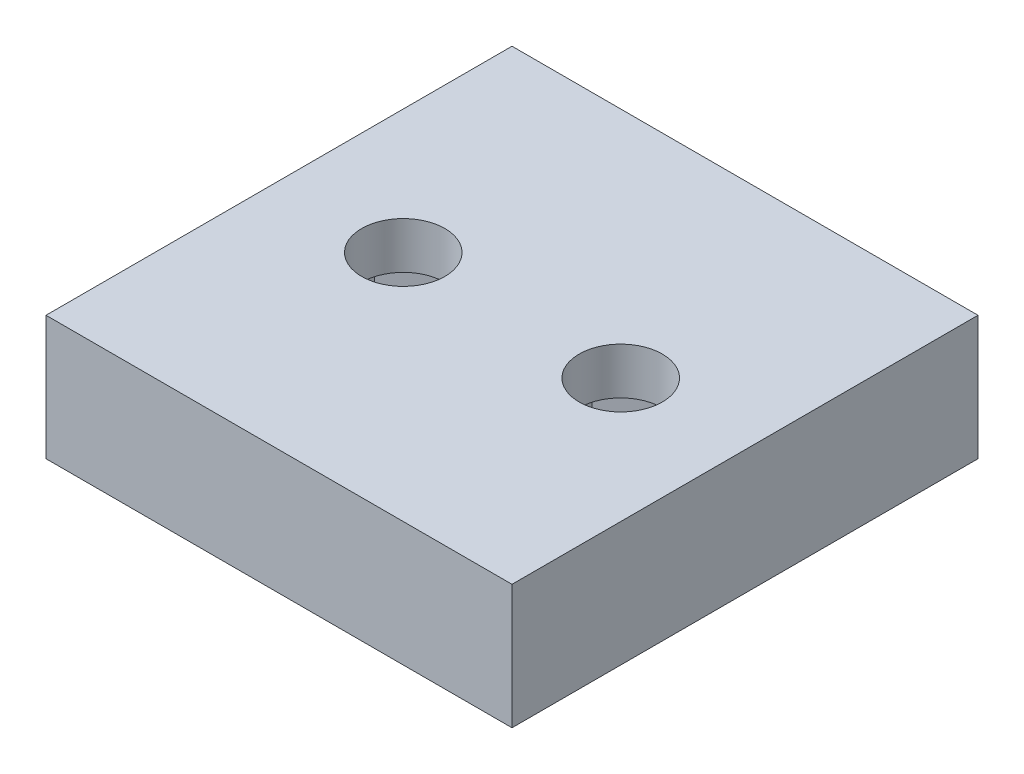
SolidWorks part; units mm, degrees
ref_plane "Front Plane" through (0, 0, 0) normal (0, 0, 1) x (1, 0, 0)
ref_plane "Top Plane" through (0, 0, 0) normal (0, 1, 0) x (1, 0, 0)
ref_plane "Right Plane" through (0, 0, 0) normal (1, 0, 0) x (0, 0, -1)
sketch "Sketch1" plane through (0, 0, 0) normal (0, 1, 0) x (1, 0, 0)
  line L1 (9.525, 9.525) -> (-9.525, 9.525)
  line L2 (9.525, 9.525) -> (9.525, -9.525)
  line L3 (9.525, -9.525) -> (-9.525, -9.525)
  line L4 (-9.525, 9.525) -> (-9.525, -9.525)
  line L5 (9.525, 9.525) -> (-9.525, -9.525) construction
  line L6 (9.525, -9.525) -> (-9.525, 9.525) construction
  point P0 (0, 0)
  dimension "D1" = 19.05
  dimension "D2" = 19.05
extrude "Boss-Extrude1" add sketch "Sketch1" along normal blind 5.08
sketch "Sketch2" plane through (0, 0, 0) normal (0, -1, 0) x (1, 0, 0)
  line L0 (-4.445, 0) -> (4.445, 0) construction
  point P3 (0, 0)
  dimension "D1" = 8.89
hole_wizard "M3 Clearance Hole1" positions "Sketch5" profile "Sketch6" hole size "M3" standard "ANSI Metric" end condition through all
sketch "Sketch5" plane through (0, 0, 0) normal (0, -1, 0) x (-1, 0, 0)
  point P0 (-4.445, 0)
  point P3 (4.445, 0)
sketch "Sketch6" plane through (4.445, 0, 0) normal (1, 0, 0) x (0, 0, -1)
  line L0 (0, 0) -> (0, 5.08)
  line L1 (0, 5.08) -> (1.7, 5.08)
  line L2 (1.7, 5.08) -> (1.7, 0)
  line L5 (1.7, 0) -> (0, 0)
  line L11 (0, -6.35) -> (0, 107.95) construction
  dimension "Thru Hole Dia." = 3.4
  dimension "Thru Hole Depth" = 5.08
sketch "Sketch8" plane through (0, 0, 0) normal (0, -1, 0) x (1, 0, 0)
  line L1 (-7.239, -1.6131) -> (-4.445, -3.2262)
  line L2 (-4.445, -3.2262) -> (-1.651, -1.6131)
  line L3 (-1.651, -1.6131) -> (-1.651, 1.6131)
  line L4 (-1.651, 1.6131) -> (-4.445, 3.2262)
  line L5 (-4.445, 3.2262) -> (-7.239, 1.6131)
  line L6 (-7.239, 1.6131) -> (-7.239, -1.6131)
  line L7 (7.239, -1.6131) -> (7.239, 1.6131)
  line L8 (7.239, 1.6131) -> (4.445, 3.2262)
  line L9 (4.445, 3.2262) -> (1.651, 1.6131)
  line L10 (1.651, 1.6131) -> (1.651, -1.6131)
  line L11 (1.651, -1.6131) -> (4.445, -3.2262)
  line L12 (4.445, -3.2262) -> (7.239, -1.6131)
  circle A0 centre (-4.445, 0) radius 2.794 construction
  circle A1 centre (4.445, 0) radius 2.794 construction
  dimension "D1" = 5.588
  dimension "D2" = 5.588
extrude "Cut-Extrude2" cut sketch "Sketch8" against normal blind 3.175
sketch "Sketch10" plane through (9.525, 0, 0) normal (1, 0, 0) x (0, 0, -1)
  line L0 (-9.525, 5.08) -> (9.525, 5.08) construction
  line L1 (3.175, 4.318) -> (-3.175, 4.318)
  line L2 (3.175, 4.318) -> (3.175, 5.08)
  line L3 (3.175, 5.08) -> (-3.175, 5.08)
  line L4 (-3.175, 4.318) -> (-3.175, 5.08)
  line L5 (3.175, 4.318) -> (-3.175, 5.08) construction
  line L6 (3.175, 5.08) -> (-3.175, 4.318) construction
  point P0 (0, 4.699)
  dimension "D1" = 6.35
  dimension "D2" = 0.762
